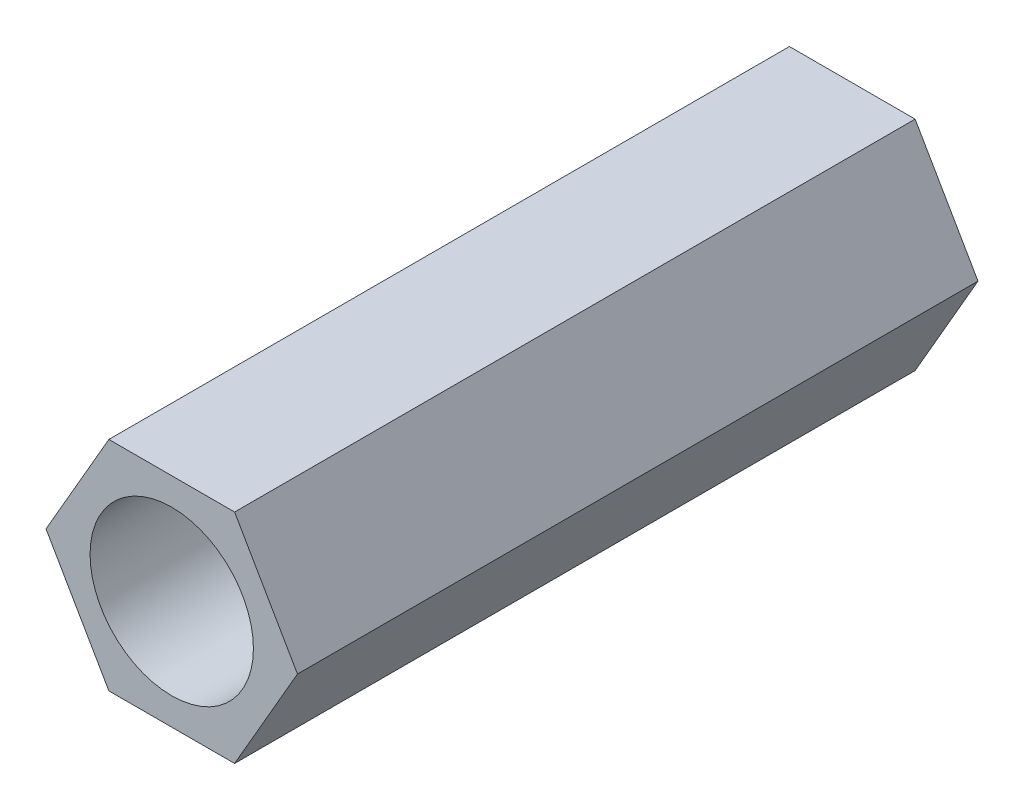
SolidWorks part; units mm, degrees
ref_plane "前视基准面" through (0, 0, 0) normal (0, 0, 1) x (1, 0, 0)
ref_plane "上视基准面" through (0, 0, 0) normal (0, 1, 0) x (1, 0, 0)
ref_plane "右视基准面" through (0, 0, 0) normal (1, 0, 0) x (0, 0, -1)
other "Configuration Table"
sketch "草图1" plane through (0, 0, 0) normal (0, 0, 1) x (1, 0, 0)
  line L1 (2.3094, 0) -> (1.1547, 2)
  line L2 (1.1547, 2) -> (-1.1547, 2)
  line L3 (-1.1547, 2) -> (-2.3094, 0)
  line L4 (-2.3094, 0) -> (-1.1547, -2)
  line L5 (-1.1547, -2) -> (1.1547, -2)
  line L6 (1.1547, -2) -> (2.3094, 0)
  circle A0 centre (0, 0) radius 2 construction
  circle A1 centre (0, 0) radius 1.5
  dimension "D1" = 2
extrude "凸台-拉伸1" add sketch "草图1" along normal blind 12.5
